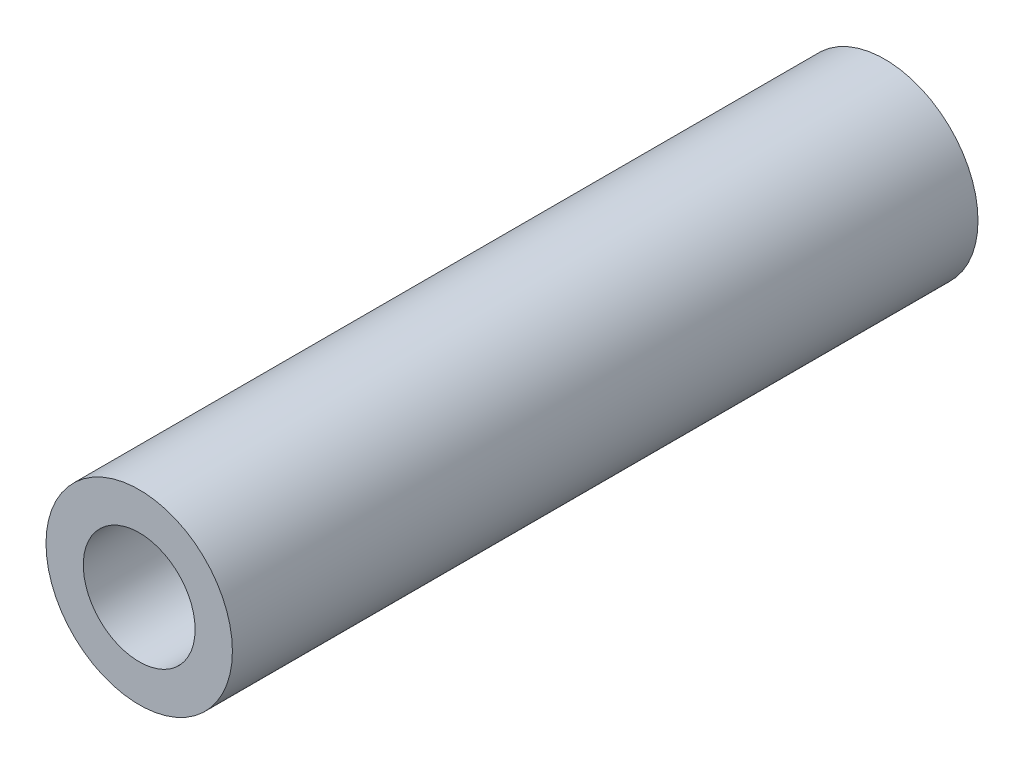
SolidWorks part; units mm, degrees
ref_plane "前视基准面" through (0, 0, 0) normal (0, 0, 1) x (1, 0, 0)
ref_plane "上视基准面" through (0, 0, 0) normal (0, 1, 0) x (1, 0, 0)
ref_plane "右视基准面" through (0, 0, 0) normal (1, 0, 0) x (0, 0, -1)
sketch "草图1" plane through (0, 0, 0) normal (0, 0, 1) x (1, 0, 0)
  circle A0 centre (0, 0) radius 7.5
  circle A1 centre (0, 0) radius 4.5
  dimension "D1" = 9
  dimension "D2" = 15
extrude "凸台-拉伸1" add sketch "草图1" along normal blind 60
